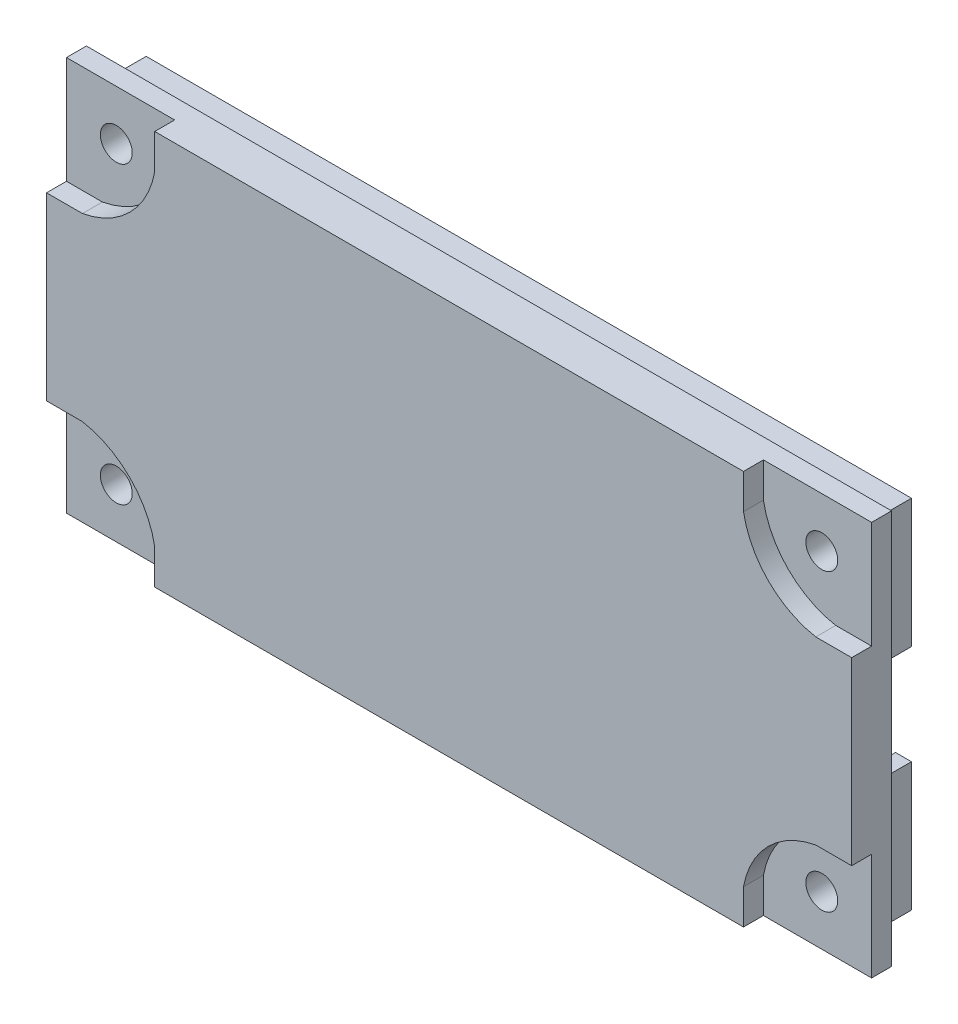
SolidWorks part; units mm, degrees
ref_plane "前基準面" through (0, 0, 0) normal (0, 0, 1) x (1, 0, 0)
ref_plane "上基準面" through (0, 0, 0) normal (0, 1, 0) x (1, 0, 0)
ref_plane "右基準面" through (0, 0, 0) normal (1, 0, 0) x (0, 0, -1)
sketch "草圖1" plane through (0, 0, 0) normal (0, 0, 1) x (1, 0, 0)
  line L1 (-20.2, 9.9) -> (20.2, 9.9)
  line L2 (-20.2, 9.9) -> (-20.2, -9.9)
  line L3 (-20.2, -9.9) -> (20.2, -9.9)
  line L4 (20.2, 9.9) -> (20.2, -9.9)
  line L5 (-20.2, 9.9) -> (20.2, -9.9) construction
  line L6 (-20.2, -9.9) -> (20.2, 9.9) construction
  point P0 (0, 0)
  dimension "D1" = 40.4
  dimension "D2" = 19.8
extrude "伸長1" add sketch "草圖1" along normal blind 2
sketch "草圖2" plane through (0, 0, 0) normal (0, 0, 1) x (-1, 0, 0)
  line L0 (0, -9.9) -> (0, 9.9) construction
  line L1 (-19.2, 8.95) -> (19.2, 8.95)
  line L2 (-19.2, 8.95) -> (-19.2, -8.95)
  line L3 (-19.2, -8.95) -> (19.2, -8.95)
  line L4 (19.2, 8.95) -> (19.2, -8.95)
  line L5 (-19.2, 8.95) -> (19.2, -8.95) construction
  line L6 (-19.2, -8.95) -> (19.2, 8.95) construction
  line L9 (20.2, 0) -> (-20.2, 0) construction
  line L12 (-15.4852, 8.15) -> (15.4852, 8.15)
  line L13 (-15.4852, -8.15) -> (15.4852, -8.15)
  line L14 (-18.4, 5.2352) -> (-18.4, -5.2352)
  line L15 (20.2, 9.9) -> (-20.2, 9.9) construction
  line L16 (18.4, 5.2352) -> (18.4, -5.2352)
  line L17 (-20.2, -9.9) -> (20.2, -9.9) construction
  arc A0 (-18.4, 5.2352) -> (-15.4852, 8.15) centre (-19.2, 8.95) ccw
  arc A1 (-18.4, -5.2352) -> (-15.4852, -8.15) centre (-19.2, -8.95) cw
  arc A2 (15.4852, 8.15) -> (18.4, 5.2352) centre (19.2, 8.95) ccw
  arc A3 (18.4, -5.2352) -> (15.4852, -8.15) centre (19.2, -8.95) ccw
  point P0 (0, 0)
  point P17 (0, 0)
  dimension "D5" = 3.8
  dimension "D1" = 38.4
  dimension "D2" = 17.9
  dimension "D3" = 0.8
  dimension "D4" = 0.8
  dimension "D6" = 0.8
  dimension "D7" = 0.8
sketch "草圖4" plane through (0, 0, 2) normal (0, 0, 1) x (-1, 0, 0)
  line L1 (-17.7, 7.4) -> (17.7, 7.4) construction
  line L2 (-17.7, 7.4) -> (-17.7, -7.4) construction
  line L3 (-17.7, -7.4) -> (17.7, -7.4) construction
  line L4 (17.7, 7.4) -> (17.7, -7.4) construction
  line L5 (-17.7, 7.4) -> (17.7, -7.4) construction
  line L6 (-17.7, -7.4) -> (17.7, 7.4) construction
  line L8 (0, 9.9) -> (0, -9.9) construction
  line L10 (20.2, 0) -> (-20.2, 0) construction
  line L12 (-20.2, -9.9) -> (20.2, -9.9) construction
  line L13 (20.2, 9.9) -> (-20.2, 9.9) construction
  line L14 (20.2, -9.9) -> (20.2, 9.9) construction
  line L15 (-20.2, 9.9) -> (-20.2, -9.9) construction
  circle A0 centre (-17.7, 7.4) radius 0.8
  circle A1 centre (17.7, 7.4) radius 0.8
  circle A2 centre (17.7, -7.4) radius 0.8
  circle A3 centre (-17.7, -7.4) radius 0.8
  point P0 (0, 0)
  dimension "D3" = 1.6
  dimension "D1" = 2.5
  dimension "D2" = 2.5
extrude "伸長2" add sketch "草圖2" against normal blind 2
sketch "草圖5" plane through (0, 0, 2) normal (0, 0, 1) x (1, 0, 0)
  line L0 (0, -9.9) -> (0, 9.9) construction
  line L1 (-19.2, 8.95) -> (19.2, 8.95) construction
  line L2 (-19.2, 8.95) -> (-19.2, -8.95) construction
  line L3 (-19.2, -8.95) -> (19.2, -8.95) construction
  line L4 (19.2, 8.95) -> (19.2, -8.95) construction
  line L5 (-19.2, 8.95) -> (19.2, -8.95) construction
  line L6 (-19.2, -8.95) -> (19.2, 8.95) construction
  line L7 (20.2, 0) -> (-20.2, 0) construction
  line L8 (-14.7717, 8.15) -> (14.7717, 8.15) construction
  line L9 (-14.7717, -8.15) -> (14.7717, -8.15) construction
  line L10 (-18.4, 4.5217) -> (-18.4, -4.5217) construction
  line L11 (18.4, 4.5217) -> (18.4, -4.5217) construction
  line L12 (-20.2, -9.9) -> (20.2, -9.9) construction
  line L13 (20.2, -9.9) -> (20.2, 9.9) construction
  line L14 (14.7717, 8.15) -> (14.7717, 9.9)
  line L15 (20.2, 9.9) -> (-20.2, 9.9) construction
  line L16 (-14.7717, 8.15) -> (-14.7717, 9.9)
  line L17 (-18.4, 4.5217) -> (-20.2, 4.5217)
  line L18 (-20.2, 9.9) -> (-20.2, -9.9) construction
  line L19 (-18.4, -4.5217) -> (-20.2, -4.5217)
  line L20 (-14.7717, -8.15) -> (-14.7717, -9.9)
  line L21 (-20.2, -9.9) -> (20.2, -9.9) construction
  line L22 (14.7717, -8.15) -> (14.7717, -9.9)
  line L23 (18.4, -4.5217) -> (20.2, -4.5217)
  line L24 (20.2, -9.9) -> (20.2, 9.9) construction
  line L25 (18.4, 4.5217) -> (20.2, 4.5217)
  line L26 (-14.7717, 9.9) -> (-20.2, 9.9)
  line L27 (20.2, 9.9) -> (14.7717, 9.9)
  line L28 (20.2, 9.9) -> (20.2, 4.5217)
  line L29 (20.2, -9.9) -> (14.7717, -9.9)
  line L30 (-20.2, 9.9) -> (-20.2, 4.5217)
  line L31 (20.2, -4.5217) -> (20.2, -9.9)
  line L32 (-14.7717, -9.9) -> (-20.2, -9.9)
  line L33 (-20.2, -4.5217) -> (-20.2, -9.9)
  arc A0 (-18.4, 4.5217) -> (-14.7717, 8.15) centre (-19.2, 8.95) ccw
  arc A1 (-18.4, -4.5217) -> (-14.7717, -8.15) centre (-19.2, -8.95) cw
  arc A2 (14.7717, 8.15) -> (18.4, 4.5217) centre (19.2, 8.95) ccw
  arc A3 (18.4, -4.5217) -> (14.7717, -8.15) centre (19.2, -8.95) ccw
  point P0 (0, 0)
  point P9 (0, 0)
  dimension "D4" = 4.5
  dimension "D1" = 38.4
  dimension "D2" = 17.9
  dimension "D3" = 0.8
  dimension "D5" = 0.8
  dimension "D6" = 0.8
  dimension "D7" = 0.8
extrude "伸長6" cut sketch "草圖5" against normal blind 1
sketch "草圖6" plane through (0, 0, 0) normal (0, 0, -1) x (-1, 0, 0)
  line L0 (-19.2, -4.45) -> (-19.2, -8.95)
  line L1 (-19.2, 8.95) -> (-14.7, 8.95)
  line L2 (-19.2, 8.95) -> (-19.2, 4.45)
  line L3 (-19.2, -8.95) -> (-14.7, -8.95)
  line L4 (19.2, 8.95) -> (19.2, 4.45)
  line L5 (14.7, -8.95) -> (19.2, -8.95)
  line L6 (14.7, 8.95) -> (19.2, 8.95)
  line L7 (19.2, -4.45) -> (19.2, -8.95)
  arc A0 (-19.2, 4.45) -> (-14.7, 8.95) centre (-19.2, 8.95) ccw
  arc A1 (14.7, 8.95) -> (19.2, 4.45) centre (19.2, 8.95) ccw
  arc A2 (19.2, -4.45) -> (14.7, -8.95) centre (19.2, -8.95) ccw
  arc A3 (-14.7, -8.95) -> (-19.2, -4.45) centre (-19.2, -8.95) ccw
  dimension "D1" = 9
extrude "伸長7" add sketch "草圖6" along normal blind 0.7
extrude "伸長4" cut sketch "草圖4" against normal through all
sketch "草圖8" plane through (20.2, 0, 0) normal (1, 0, 0) x (0, 0, -1)
  line L0 (1, 0) -> (2, 0) construction
  line L1 (0, -2.5) -> (2, -2.5)
  line L2 (0, -2.5) -> (0, 2.5)
  line L3 (0, 2.5) -> (2, 2.5)
  line L4 (2, -2.5) -> (2, 2.5)
  line L5 (0, -2.5) -> (2, 2.5) construction
  line L6 (0, 2.5) -> (2, -2.5) construction
  line L7 (2, -8.95) -> (2, 8.95) construction
  point P0 (1, 0)
  dimension "D1" = 2
  dimension "D2" = 5
extrude "伸長8" cut sketch "草圖8" against normal up to surface (1.8 mm away) up to face at (18.4, 0, -0.85)
